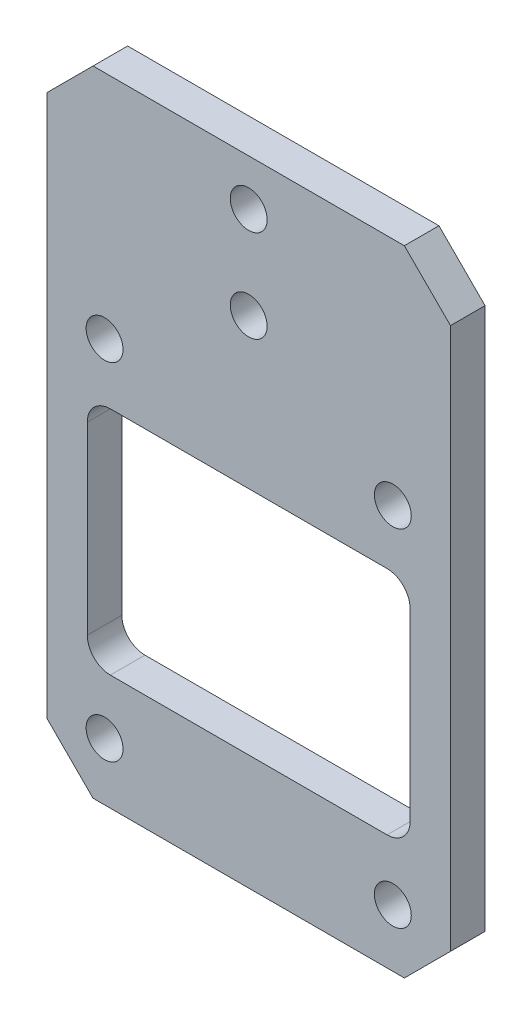
SolidWorks part; units mm, degrees
ref_plane "前基準面" through (0, 0, 0) normal (0, 0, 1) x (1, 0, 0)
ref_plane "上基準面" through (0, 0, 0) normal (0, 1, 0) x (1, 0, 0)
ref_plane "右基準面" through (0, 0, 0) normal (1, 0, 0) x (0, 0, -1)
sketch "草圖1" plane through (0, 0, 0) normal (0, 0, 1) x (1, 0, 0)
  line L1 (17.5, -27.5) -> (-17.5, -27.5)
  line L2 (17.5, -27.5) -> (17.5, 27.5)
  line L3 (17.5, 27.5) -> (-17.5, 27.5)
  line L4 (-17.5, -27.5) -> (-17.5, 27.5)
  line L5 (17.5, -27.5) -> (-17.5, 27.5) construction
  line L6 (17.5, 27.5) -> (-17.5, -27.5) construction
  point P0 (0, 0)
  dimension "D1" = 35
  dimension "D2" = 55
extrude "填料-伸長1" add sketch "草圖1" along normal blind 3
chamfer "導角1" distance 4 angle 45 4 edges at (-17.5, -27.5, 1.5) (17.5, -27.5, 1.5) (17.5, 27.5, 1.5) (-17.5, 27.5, 1.5)
sketch "草圖2" plane through (0, 0, 3) normal (0, 0, 1) x (1, 0, 0)
  line L0 (0, -27.5) -> (0, -7.5) construction
  line L5 (-13.5, -27.5) -> (13.5, -27.5) construction
  line L7 (12.5, 7.5) -> (-12.5, 7.5) construction
  line L8 (12.5, 7.5) -> (12.5, -22.5) construction
  line L9 (12.5, -22.5) -> (-12.5, -22.5) construction
  line L10 (-12.5, 7.5) -> (-12.5, -22.5) construction
  line L11 (12.5, 7.5) -> (-12.5, -22.5) construction
  line L12 (12.5, -22.5) -> (-12.5, 7.5) construction
  circle A1 centre (-12.5, 7.5) radius 1.6
  dimension "D3" = 20
  dimension "D4" = 3.2
  dimension "D1" = 25
  dimension "D2" = 30
extrude "除料-伸長1" cut sketch "草圖2" against normal through all
pattern_linear "直線複製排列1" count 2 spacing 25 along (1, 0, 0) count 2 spacing 30 along (0, -1, 0) of "除料-伸長1"
sketch "草圖3" plane through (0, 0, 3) normal (0, 0, 1) x (1, 0, 0)
  line L0 (0, 27.5) -> (0, 23.5) construction
  line L1 (13.5, 27.5) -> (-13.5, 27.5) construction
  circle A0 centre (0, 23.5) radius 1.6
  dimension "D1" = 4
  dimension "D2" = 3.2
extrude "除料-伸長2" cut sketch "草圖3" against normal through all
pattern_linear "直線複製排列2" count 2 spacing 8 along (0, -1, 0) of "除料-伸長2"
sketch "草圖4" plane through (0, 0, 3) normal (0, 0, 1) x (1, 0, 0)
  line L0 (-13.5, -27.5) -> (13.5, -27.5) construction
  line L1 (14, -17.5) -> (-14, -17.5)
  line L2 (14, -17.5) -> (14, 2.5)
  line L3 (14, 2.5) -> (-14, 2.5)
  line L4 (-14, -17.5) -> (-14, 2.5)
  line L5 (14, -17.5) -> (-14, 2.5) construction
  line L6 (14, 2.5) -> (-14, -17.5) construction
  point P0 (0, -7.5)
  dimension "D1" = 20
  dimension "D2" = 28
  dimension "D3" = 20
extrude "除料-伸長3" cut sketch "草圖4" against normal through all
fillet "圓角1" radius 2 4 edges at (14, 2.5, 1.5) (14, -17.5, 1.5) (-14, -17.5, 1.5) (-14, 2.5, 1.5)
